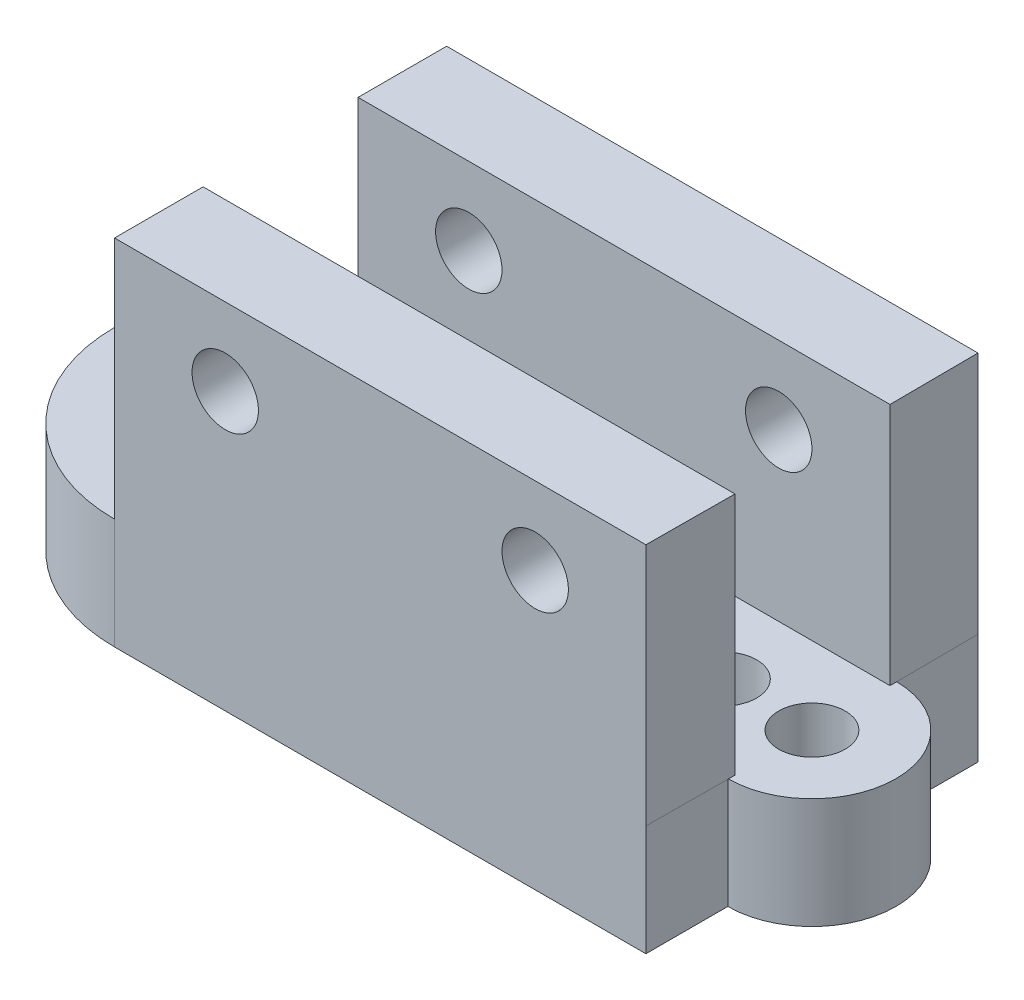
SolidWorks part; units mm, degrees
ref_plane "Front Plane" through (0, 0, 0) normal (0, 0, 1) x (1, 0, 0)
ref_plane "Top Plane" through (0, 0, 0) normal (0, 1, 0) x (1, 0, 0)
ref_plane "Right Plane" through (0, 0, 0) normal (1, 0, 0) x (0, 0, -1)
sketch "Sketch1" plane through (0, 0, 0) normal (0, 1, 0) x (1, 0, 0)
  line L2 (20, 0) -> (24, 0)
  line L3 (24, 0) -> (27.8, 0)
  line L4 (24, 0) -> (24, -3.8)
  line L5 (24, 0) -> (24, 3.8)
  line L7 (0, 7.5) -> (24, 7.5)
  line L8 (0, -7.5) -> (24, -7.5)
  line L9 (24, -7.5) -> (24, -3.8)
  line L11 (24, 7.5) -> (24, 3.8)
  circle A0 centre (0, 0) radius 7.5
  arc A1 (24, 3.8) -> (24, -3.8) centre (24, 0) cw
  circle A3 centre (20, 0) radius 1.5
  circle A4 centre (24, 0) radius 1.5
  circle A5 centre (0, 0) radius 1.5
  dimension "D7" = 15
  dimension "D2" = 20
  dimension "D3" = 4
  dimension "D4" = 3.8
  dimension "D5" = 3.8
  dimension "D6" = 3.8
  dimension "D8" = 24
extrude "Boss-Extrude1" add sketch "Sketch1" along normal blind 5
sketch "Sketch2" plane through (0, 5, 0) normal (0, 1, 0) x (1, 0, 0)
  line L0 (0, -7.5) -> (0, -3.5)
  line L1 (0, -3.5) -> (24.0247, -3.5)
  line L2 (24.0247, -3.5) -> (24, -7.5)
  line L3 (24, -7.5) -> (0, -7.5)
  line L5 (24.0247, 3.5) -> (24, 7.5)
  line L6 (0, 3.5) -> (24.0247, 3.5)
  line L7 (0, 7.5) -> (0, 3.5)
  line L8 (24, 7.5) -> (0, 7.5)
  dimension "D1" = 4
  dimension "D2" = 4
  dimension "D3" = 24
extrude "Boss-Extrude2" add sketch "Sketch2" along normal blind 11
sketch "Sketch3" plane through (0, 5, 0) normal (0, 1, 0) x (1, 0, 0)
  line L0 (0, 0) -> (20, 0)
  line L1 (10, 0) -> (10, 3.5)
  line L2 (0, 3.5) -> (24.0247, 3.5) construction
  line L3 (10, 3.5) -> (12, 3.5)
  line L4 (12, 3.5) -> (12, -3.5)
  line L5 (24.0247, -3.5) -> (0, -3.5) construction
  line L6 (12, -3.5) -> (8, -3.5)
  line L7 (8, -3.5) -> (8, 3.5)
  line L8 (8, 3.5) -> (10, 3.5)
  line M11 (24.0247, 3.5) -> (0, 3.5)
  line M15 (0, -3.5) -> (24.0247, -3.5)
  dimension "D1" = 2
  dimension "D2" = 4
extrude "Boss-Extrude3" add sketch "Sketch3" along normal blind 4 contours L7 L4 L0 M15 | L4 L1 L0 M11 | L7 L0 L1 M11
hole_wizard "Ø3.0 (3) Diameter Hole2" positions "Sketch4" profile "Sketch5" hole size "Ø3.0" standard "ISO" end condition through all
sketch "Sketch4" plane through (0, 0, 7.5) normal (0, 0, 1) x (1, 0, 0)
  line L0 (0, 16) -> (0, 9)
  line L1 (0, 16) -> (0, 5) construction
  line L3 (0, 12.5) -> (5, 12.5)
  line L4 (5, 12.5) -> (19, 12.5)
  line L5 (19, 12.5) -> (24, 12.5)
  line L6 (24, 16) -> (24, 5) construction
  point P9 (5, 12.5)
  point P11 (19, 12.5)
  dimension "D1" = 7
  dimension "D2" = 5
  dimension "D3" = 5
  dimension "D4" = 14
sketch "Sketch5" plane through (19, 12.5, 7.5) normal (1, 0, 0) x (0, -1, 0)
  line L0 (0, 0) -> (0, 15)
  line L1 (0, 15) -> (1.5, 15)
  line L2 (1.5, 15) -> (1.5, 0)
  line L5 (1.5, 0) -> (0, 0)
  line L11 (0, -6.35) -> (0, 107.95) construction
  dimension "Thru Hole Dia." = 3
  dimension "Thru Hole Depth" = 15
